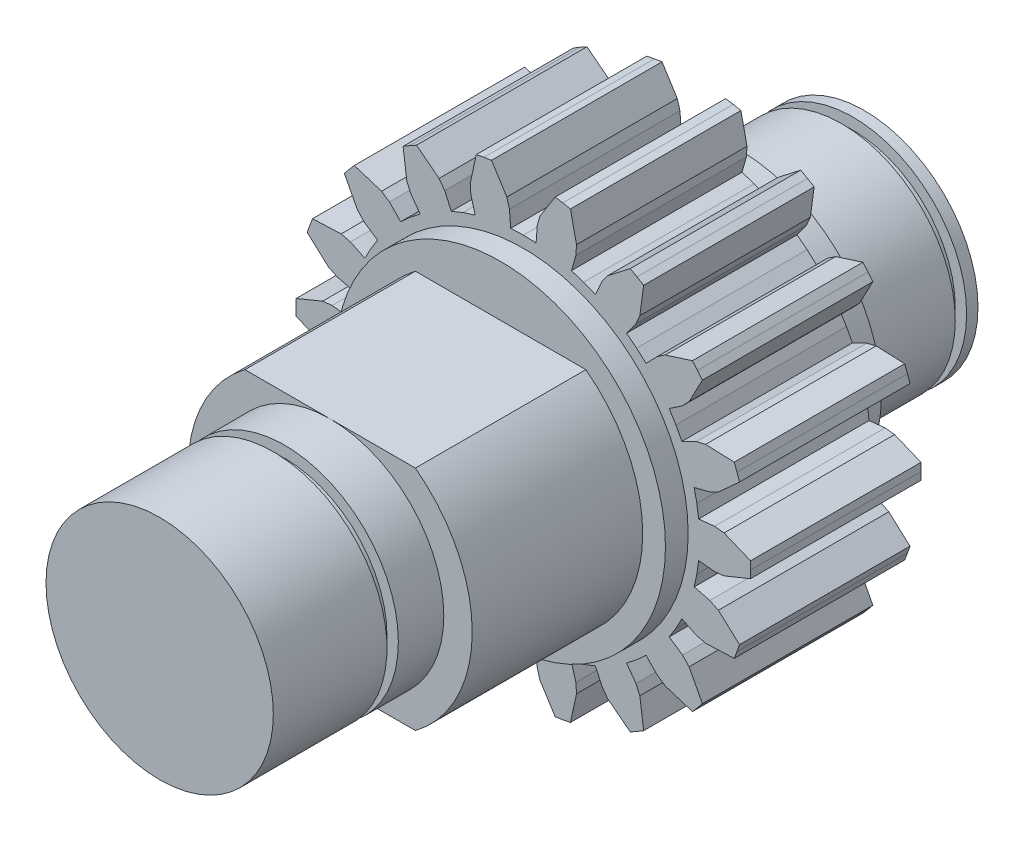
SolidWorks part; units mm, degrees
ref_plane "Front Plane" through (0, 0, 0) normal (0, 0, 1) x (1, 0, 0)
ref_plane "Top Plane" through (0, 0, 0) normal (0, 1, 0) x (1, 0, 0)
ref_plane "Right Plane" through (0, 0, 0) normal (1, 0, 0) x (0, 0, -1)
sketch "Sketch1" plane through (0, 0, 0) normal (0, 0, 1) x (1, 0, 0)
  line L0 (15.4192, -1.5809) -> (16.8263, -1.7252)
  line L1 (16.8263, -1.7252) -> (17.6608, -1.6345)
  line L2 (17.6608, -1.6345) -> (19.9884, -0.6815)
  line L3 (19.9884, -0.6815) -> (20, 0)
  line L4 (20, 0) -> (19.9884, 0.6815)
  line L5 (19.9884, 0.6815) -> (17.6608, 1.6345)
  line L6 (17.6608, 1.6345) -> (16.8263, 1.7252)
  line L7 (16.8263, 1.7252) -> (15.4192, 1.5809)
  line L8 (15.4192, 1.5809) -> (15.2645, 2.6915)
  line L9 (15.2645, 2.6915) -> (15.03, 3.7881)
  line L10 (15.03, 3.7881) -> (16.4016, 4.1338)
  line L11 (16.4016, 4.1338) -> (17.1547, 4.5044)
  line L12 (17.1547, 4.5044) -> (19.016, 6.196)
  line L13 (19.016, 6.196) -> (18.7939, 6.8404)
  line L14 (18.7939, 6.8404) -> (18.5498, 7.4769)
  line L15 (18.5498, 7.4769) -> (16.0367, 7.5763)
  line L16 (16.0367, 7.5763) -> (15.2215, 7.376)
  line L17 (15.2215, 7.376) -> (13.9486, 6.7592)
  line L18 (13.9486, 6.7592) -> (13.4234, 7.75)
  line L19 (13.4234, 7.75) -> (12.8279, 8.7002)
  line L20 (12.8279, 8.7002) -> (13.9986, 9.4942)
  line L21 (13.9986, 9.4942) -> (14.5796, 10.1)
  line L22 (14.5796, 10.1) -> (15.7501, 12.3262)
  line L23 (15.7501, 12.3262) -> (15.3209, 12.8558)
  line L24 (15.3209, 12.8558) -> (14.8739, 13.3704)
  line L25 (14.8739, 13.3704) -> (12.4783, 12.6042)
  line L26 (12.4783, 12.6042) -> (11.7808, 12.1373)
  line L27 (11.7808, 12.1373) -> (10.7956, 11.1223)
  line L28 (10.7956, 11.1223) -> (9.9632, 11.8737)
  line L29 (9.9632, 11.8737) -> (9.0787, 12.5629)
  line L30 (9.0787, 12.5629) -> (9.9072, 13.7094)
  line L31 (9.9072, 13.7094) -> (10.2459, 14.4774)
  line L32 (10.2459, 14.4774) -> (10.5844, 16.9697)
  line L33 (10.5844, 16.9697) -> (10, 17.3205)
  line L34 (10, 17.3205) -> (9.404, 17.6512)
  line L35 (9.404, 17.6512) -> (7.4148, 16.1119)
  line L36 (7.4148, 16.1119) -> (6.9191, 15.4345)
  line L37 (6.9191, 15.4345) -> (6.3405, 14.1438)
  line L38 (6.3405, 14.1438) -> (5.3013, 14.5652)
  line L39 (5.3013, 14.5652) -> (4.2344, 14.9104)
  line L40 (4.2344, 14.9104) -> (4.6208, 16.2711)
  line L41 (4.6208, 16.2711) -> (4.6764, 17.1086)
  line L42 (4.6764, 17.1086) -> (4.1421, 19.5664)
  line L43 (4.1421, 19.5664) -> (3.473, 19.6962)
  line L44 (3.473, 19.6962) -> (2.7998, 19.8031)
  line L45 (2.7998, 19.8031) -> (1.4571, 17.6763)
  line L46 (1.4571, 17.6763) -> (1.2229, 16.8702)
  line L47 (1.2229, 16.8702) -> (1.1206, 15.4594)
  line L48 (1.1206, 15.4594) -> (0, 15.5)
  line L49 (0, 15.5) -> (-1.1206, 15.4594)
  line L50 (-1.1206, 15.4594) -> (-1.2229, 16.8702)
  line L51 (-1.2229, 16.8702) -> (-1.4571, 17.6763)
  line L52 (-1.4571, 17.6763) -> (-2.7998, 19.8031)
  line L53 (-2.7998, 19.8031) -> (-3.473, 19.6962)
  line L54 (-3.473, 19.6962) -> (-4.1421, 19.5664)
  line L55 (-4.1421, 19.5664) -> (-4.6764, 17.1086)
  line L56 (-4.6764, 17.1086) -> (-4.6208, 16.2711)
  line L57 (-4.6208, 16.2711) -> (-4.2344, 14.9104)
  line L58 (-4.2344, 14.9104) -> (-5.3013, 14.5652)
  line L59 (-5.3013, 14.5652) -> (-6.3405, 14.1438)
  line L60 (-6.3405, 14.1438) -> (-6.9191, 15.4345)
  line L61 (-6.9191, 15.4345) -> (-7.4148, 16.1119)
  line L62 (-7.4148, 16.1119) -> (-9.404, 17.6512)
  line L63 (-9.404, 17.6512) -> (-10, 17.3205)
  line L64 (-10, 17.3205) -> (-10.5844, 16.9697)
  line L65 (-10.5844, 16.9697) -> (-10.2459, 14.4774)
  line L66 (-10.2459, 14.4774) -> (-9.9072, 13.7094)
  line L67 (-9.9072, 13.7094) -> (-9.0787, 12.5629)
  line L68 (-9.0787, 12.5629) -> (-9.9632, 11.8737)
  line L69 (-9.9632, 11.8737) -> (-10.7956, 11.1223)
  line L70 (-10.7956, 11.1223) -> (-11.7808, 12.1373)
  line L71 (-11.7808, 12.1373) -> (-12.4783, 12.6042)
  line L72 (-12.4783, 12.6042) -> (-14.8739, 13.3704)
  line L73 (-14.8739, 13.3704) -> (-15.3209, 12.8558)
  line L74 (-15.3209, 12.8558) -> (-15.7501, 12.3262)
  line L75 (-15.7501, 12.3262) -> (-14.5796, 10.1)
  line L76 (-14.5796, 10.1) -> (-13.9986, 9.4942)
  line L77 (-13.9986, 9.4942) -> (-12.8279, 8.7002)
  line L78 (-12.8279, 8.7002) -> (-13.4234, 7.75)
  line L79 (-13.4234, 7.75) -> (-13.9486, 6.7592)
  line L80 (-13.9486, 6.7592) -> (-15.2215, 7.376)
  line L81 (-15.2215, 7.376) -> (-16.0367, 7.5763)
  line L82 (-16.0367, 7.5763) -> (-18.5498, 7.4769)
  line L83 (-18.5498, 7.4769) -> (-18.7939, 6.8404)
  line L84 (-18.7939, 6.8404) -> (-19.016, 6.196)
  line L85 (-19.016, 6.196) -> (-17.1547, 4.5044)
  line L86 (-17.1547, 4.5044) -> (-16.4016, 4.1338)
  line L87 (-16.4016, 4.1338) -> (-15.03, 3.7881)
  line L88 (-15.03, 3.7881) -> (-15.2645, 2.6915)
  line L89 (-15.2645, 2.6915) -> (-15.4192, 1.5809)
  line L90 (-15.4192, 1.5809) -> (-16.8263, 1.7252)
  line L91 (-16.8263, 1.7252) -> (-17.6608, 1.6345)
  line L92 (-17.6608, 1.6345) -> (-19.9884, 0.6815)
  line L93 (-19.9884, 0.6815) -> (-20, 0)
  line L94 (-20, 0) -> (-19.9884, -0.6815)
  line L95 (-19.9884, -0.6815) -> (-17.6608, -1.6345)
  line L96 (-17.6608, -1.6345) -> (-16.8263, -1.7252)
  line L97 (-16.8263, -1.7252) -> (-15.4192, -1.5809)
  line L98 (-15.4192, -1.5809) -> (-15.2645, -2.6915)
  line L99 (-15.2645, -2.6915) -> (-15.03, -3.7881)
  line L100 (-15.03, -3.7881) -> (-16.4016, -4.1338)
  line L101 (-16.4016, -4.1338) -> (-17.1547, -4.5044)
  line L102 (-17.1547, -4.5044) -> (-19.016, -6.196)
  line L103 (-19.016, -6.196) -> (-18.7939, -6.8404)
  line L104 (-18.7939, -6.8404) -> (-18.5498, -7.4769)
  line L105 (-18.5498, -7.4769) -> (-16.0367, -7.5763)
  line L106 (-16.0367, -7.5763) -> (-15.2215, -7.376)
  line L107 (-15.2215, -7.376) -> (-13.9486, -6.7592)
  line L108 (-13.9486, -6.7592) -> (-13.4234, -7.75)
  line L109 (-13.4234, -7.75) -> (-12.8279, -8.7002)
  line L110 (-12.8279, -8.7002) -> (-13.9986, -9.4942)
  line L111 (-13.9986, -9.4942) -> (-14.5796, -10.1)
  line L112 (-14.5796, -10.1) -> (-15.7501, -12.3262)
  line L113 (-15.7501, -12.3262) -> (-15.3209, -12.8558)
  line L114 (-15.3209, -12.8558) -> (-14.8739, -13.3704)
  line L115 (-14.8739, -13.3704) -> (-12.4783, -12.6042)
  line L116 (-12.4783, -12.6042) -> (-11.7808, -12.1373)
  line L117 (-11.7808, -12.1373) -> (-10.7956, -11.1223)
  line L118 (-10.7956, -11.1223) -> (-9.9632, -11.8737)
  line L119 (-9.9632, -11.8737) -> (-9.0787, -12.5629)
  line L120 (-9.0787, -12.5629) -> (-9.9072, -13.7094)
  line L121 (-9.9072, -13.7094) -> (-10.2459, -14.4774)
  line L122 (-10.2459, -14.4774) -> (-10.5844, -16.9697)
  line L123 (-10.5844, -16.9697) -> (-10, -17.3205)
  line L124 (-10, -17.3205) -> (-9.404, -17.6512)
  line L125 (-9.404, -17.6512) -> (-7.4148, -16.1119)
  line L126 (-7.4148, -16.1119) -> (-6.9191, -15.4345)
  line L127 (-6.9191, -15.4345) -> (-6.3405, -14.1438)
  line L128 (-6.3405, -14.1438) -> (-5.3013, -14.5652)
  line L129 (-5.3013, -14.5652) -> (-4.2344, -14.9104)
  line L130 (-4.2344, -14.9104) -> (-4.6208, -16.2711)
  line L131 (-4.6208, -16.2711) -> (-4.6764, -17.1086)
  line L132 (-4.6764, -17.1086) -> (-4.1421, -19.5664)
  line L133 (-4.1421, -19.5664) -> (-3.473, -19.6962)
  line L134 (-3.473, -19.6962) -> (-2.7998, -19.8031)
  line L135 (-2.7998, -19.8031) -> (-1.4571, -17.6763)
  line L136 (-1.4571, -17.6763) -> (-1.2229, -16.8702)
  line L137 (-1.2229, -16.8702) -> (-1.1206, -15.4594)
  line L138 (-1.1206, -15.4594) -> (0, -15.5)
  line L139 (0, -15.5) -> (1.1206, -15.4594)
  line L140 (1.1206, -15.4594) -> (1.2229, -16.8702)
  line L141 (1.2229, -16.8702) -> (1.4571, -17.6763)
  line L142 (1.4571, -17.6763) -> (2.7998, -19.8031)
  line L143 (2.7998, -19.8031) -> (3.473, -19.6962)
  line L144 (3.473, -19.6962) -> (4.1421, -19.5664)
  line L145 (4.1421, -19.5664) -> (4.6764, -17.1086)
  line L146 (4.6764, -17.1086) -> (4.6208, -16.2711)
  line L147 (4.6208, -16.2711) -> (4.2344, -14.9104)
  line L148 (4.2344, -14.9104) -> (5.3013, -14.5652)
  line L149 (5.3013, -14.5652) -> (6.3405, -14.1438)
  line L150 (6.3405, -14.1438) -> (6.9191, -15.4345)
  line L151 (6.9191, -15.4345) -> (7.4148, -16.1119)
  line L152 (7.4148, -16.1119) -> (9.404, -17.6512)
  line L153 (9.404, -17.6512) -> (10, -17.3205)
  line L154 (10, -17.3205) -> (10.5844, -16.9697)
  line L155 (10.5844, -16.9697) -> (10.2459, -14.4774)
  line L156 (10.2459, -14.4774) -> (9.9072, -13.7094)
  line L157 (9.9072, -13.7094) -> (9.0787, -12.5629)
  line L158 (9.0787, -12.5629) -> (9.9632, -11.8737)
  line L159 (9.9632, -11.8737) -> (10.7956, -11.1223)
  line L160 (10.7956, -11.1223) -> (11.7808, -12.1373)
  line L161 (11.7808, -12.1373) -> (12.4783, -12.6042)
  line L162 (12.4783, -12.6042) -> (14.8739, -13.3704)
  line L163 (14.8739, -13.3704) -> (15.3209, -12.8558)
  line L164 (15.3209, -12.8558) -> (15.7501, -12.3262)
  line L165 (15.7501, -12.3262) -> (14.5796, -10.1)
  line L166 (14.5796, -10.1) -> (13.9986, -9.4942)
  line L167 (13.9986, -9.4942) -> (12.8279, -8.7002)
  line L168 (12.8279, -8.7002) -> (13.4234, -7.75)
  line L169 (13.4234, -7.75) -> (13.9486, -6.7592)
  line L170 (13.9486, -6.7592) -> (15.2215, -7.376)
  line L171 (15.2215, -7.376) -> (16.0367, -7.5763)
  line L172 (16.0367, -7.5763) -> (18.5498, -7.4769)
  line L173 (18.5498, -7.4769) -> (18.7939, -6.8404)
  line L174 (18.7939, -6.8404) -> (19.016, -6.196)
  line L175 (19.016, -6.196) -> (17.1547, -4.5044)
  line L176 (17.1547, -4.5044) -> (16.4016, -4.1338)
  line L177 (16.4016, -4.1338) -> (15.03, -3.7881)
  line L178 (15.03, -3.7881) -> (15.2645, -2.6915)
  line L179 (15.2645, -2.6915) -> (15.4192, -1.5809)
extrude "Gear_C_18T_Involute" add sketch "Sketch1" along normal blind 15
sketch "Sketch2" plane through (0, 0, 0) normal (0, 0, 1) x (1, 0, 0)
  circle A0 centre (0, 0) radius 12.5
extrude "Left_Collar_D25x4" add sketch "Sketch2" against normal blind 4
sketch "Sketch3" plane through (0, 0, 0) normal (0, 0, 1) x (1, 0, 0)
  circle A0 centre (0, 0) radius 10
extrude "Left_Shaft_D20x15" add sketch "Sketch3" against normal blind 15
ref_plane "Plane_GearFace_15mm" through (0, 0, 15) normal (0, 0, 1) x (1, 0, 0)
sketch "Sketch4" plane through (0, 0, 15) normal (0, 0, 1) x (1, 0, 0)
  circle A0 centre (0, 0) radius 14.5
extrude "Right_Shoulder_D29x2" add sketch "Sketch4" along normal blind 2
ref_plane "Plane_SeatStart_17mm" through (0, 0, 17) normal (0, 0, 1) x (1, 0, 0)
sketch "Sketch5" plane through (0, 0, 17) normal (0, 0, 1) x (1, 0, 0)
  circle A0 centre (0, 0) radius 12.5
extrude "Right_GearB_Seat_D25x15" add sketch "Sketch5" along normal blind 15
ref_plane "Plane_StubStart_32mm" through (0, 0, 32) normal (0, 0, 1) x (1, 0, 0)
sketch "Sketch6" plane through (0, 0, 32) normal (0, 0, 1) x (1, 0, 0)
  circle A0 centre (0, 0) radius 10
extrude "Right_Stub_D20x15" add sketch "Sketch6" along normal blind 15
sketch "Sketch7" plane through (0, 0, 17) normal (0, 0, 1) x (1, 0, 0)
  line L1 (-14, 10) -> (14, 10)
  line L2 (-14, 10) -> (-14, 14)
  line L3 (-14, 14) -> (14, 14)
  line L4 (14, 10) -> (14, 14)
  line L6 (-14, -10) -> (14, -10)
  line L7 (-14, -10) -> (-14, -14)
  line L8 (-14, -14) -> (14, -14)
  line L9 (14, -10) -> (14, -14)
extrude "Double_Flat_Cut_20mm" cut sketch "Sketch7" along normal blind 15
sketch "Sketch8" plane through (0, 0, 0) normal (1, 0, 0) x (0, 0, -1)
  line L0 (-50, 0) -> (50, 0) construction
  line L2 (14, 9) -> (13, 9)
  line L3 (14, 9) -> (14, 11)
  line L4 (14, 11) -> (13, 11)
  line L5 (13, 9) -> (13, 11)
revolve "Left_SnapRing_Groove_D18" cut sketch "Sketch8" angle 360 about L0
sketch "Sketch9" plane through (0, 0, 0) normal (1, 0, 0) x (0, 0, -1)
  line L0 (-50, 0) -> (50, 0) construction
  line L2 (-36, 9) -> (-37, 9)
  line L3 (-36, 9) -> (-36, 11)
  line L4 (-36, 11) -> (-37, 11)
  line L5 (-37, 9) -> (-37, 11)
revolve "Right_SnapRing_Groove_D18" cut sketch "Sketch9" angle 360 about L0
